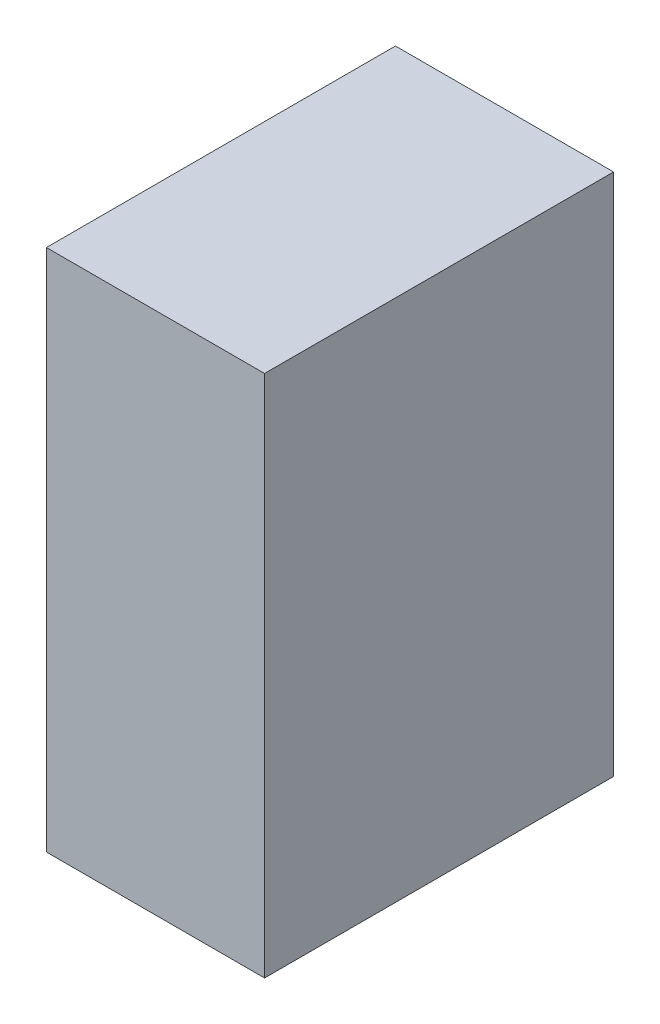
SolidWorks part; units mm, degrees
ref_plane "Front Plane" through (0, 0, 0) normal (0, 0, 1) x (1, 0, 0)
ref_plane "Top Plane" through (0, 0, 0) normal (0, 1, 0) x (1, 0, 0)
ref_plane "Right Plane" through (0, 0, 0) normal (1, 0, 0) x (0, 0, -1)
sketch "Sketch1" plane through (0, 0, 0) normal (0, 0, 1) x (1, 0, 0)
  line L1 (0, 0) -> (0.25, 0)
  line L2 (0, 0) -> (0, 0.6)
  line L3 (0, 0.6) -> (0.25, 0.6)
  line L4 (0.25, 0) -> (0.25, 0.6)
  dimension "D1" = 0.25
  dimension "D2" = 0.6
extrude "Boss-Extrude1" add sketch "Sketch1" along normal blind 0.4 contours L2 L3 L4 L1
equation "\"t\"= 0.25'thickness of the sheets"
equation "\"t_cf\" = 0.115'thickness of single carbon fiber layer"
equation "\"t_kapton\" = 0.025'thickness of single Kapton flex layer"
equation "\"t_fr4\" = 0.1'thickness of FR4 with copper layer"
equation "\"joint_flex\"= 0.1'Width of flextures gap"
equation "\"joint_flex_eff\"= 0.02'Width of flecture after castelation"
equation "\"joint_fold\"= 0.2'Width of folding joints for 90deg fold"
equation "\"gap_tolerance\"= 0.002'Width to have interfecence fit between carbon fiber inserts"
equation "\"assemble_angle\"= 90'Angle of assembly parts"
equation "\"link_lift\"= 0.5'Actuation linkage amplification for the lift motion"
equation "\"link_swing\"= 0.45'Actuation linkage amplification for the swing motion"
equation "\"D1@Sketch1\"=\"t\""
equation "\"D1@Boss-Extrude1\"=\"joint_fold\"*2"
